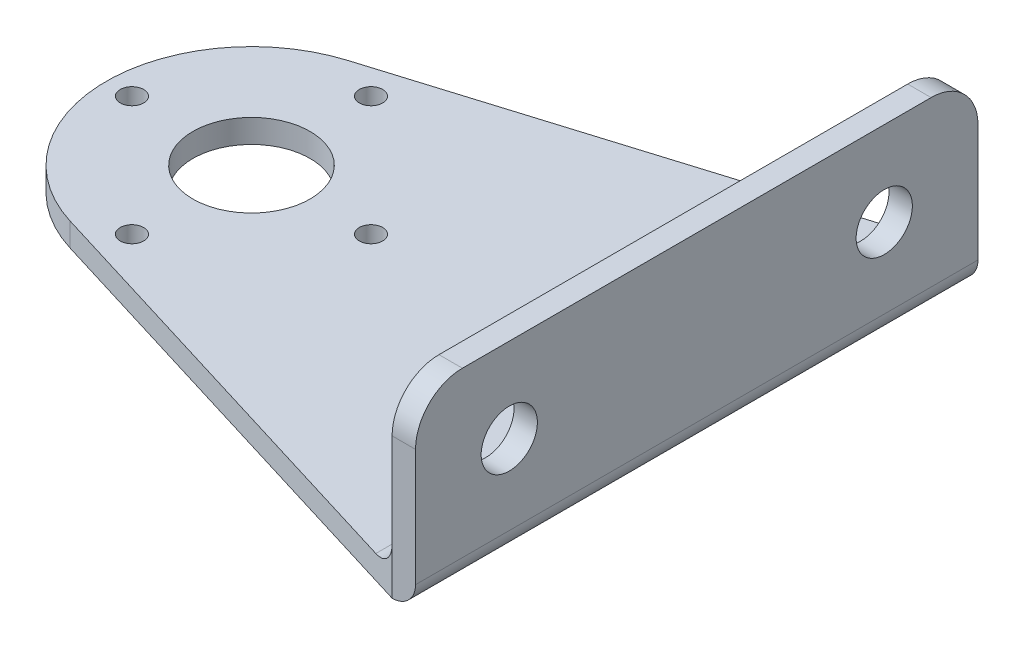
SolidWorks part; units mm, degrees
material "PBT General Purpose"
ref_plane "Front Plane" through (0, 0, 0) normal (0, 0, 1) x (1, 0, 0)
ref_plane "Top Plane" through (0, 0, 0) normal (0, 1, 0) x (1, 0, 0)
ref_plane "Right Plane" through (0, 0, 0) normal (1, 0, 0) x (0, 0, -1)
sketch "Sketch1" plane through (0, 0, 0) normal (0, 1, 0) x (1, 0, 0)
  line L0 (0, 0) -> (90, 0) construction
  line L1 (90, 60) -> (90, -60)
  line L2 (90, 60) -> (-9.0821, 29.6398)
  line L3 (90, -60) -> (-9.0821, -29.6398)
  arc A0 (-9.0821, 29.6398) -> (-9.0821, -29.6398) centre (0, 0) ccw
  circle A1 centre (0, 0) radius 25.5 construction
  circle A2 centre (0, 25.5) radius 2.5
  circle A3 centre (-25.5, 0) radius 2.5
  circle A4 centre (25.5, 0) radius 2.5
  circle A5 centre (0, -25.5) radius 2.5
  circle A6 centre (0, 0) radius 12.5
  point P7 (90, 0)
  dimension "D1" = 62
  dimension "D4" = 51
  dimension "D5" = 5
  dimension "D6" = 25
  dimension "D2" = 90
  dimension "D3" = 120
extrude "Boss-Extrude1" add sketch "Sketch1" along normal blind 5
sketch "Sketch2" plane through (90, 0, 0) normal (1, 0, 0) x (0, 0, -1)
  line L0 (60, 5) -> (60, 0) construction
  line L1 (-60, 0) -> (60, 0)
  line L2 (-60, 0) -> (-60, 30)
  line L3 (-50, 40) -> (50, 40)
  line L4 (60, 0) -> (60, 30)
  arc A0 (50, 40) -> (60, 30) centre (50, 30) cw
  arc A1 (-60, 30) -> (-50, 40) centre (-50, 30) cw
  point P9 (60, 40)
  dimension "D2" = 10
  dimension "D1" = 40
extrude "Boss-Extrude2" add sketch "Sketch2" along normal blind 5
fillet "Fillet1" radius 5 2 edges at (95, 0, 0) (90, 5, 0)
sketch "Sketch3" plane through (95, 0, 0) normal (1, 0, 0) x (0, 0, -1)
  line L0 (-40, 22) -> (40, 22) construction
  line L1 (50, 40) -> (-50, 40) construction
  circle A0 centre (-40, 22) radius 6
  circle A1 centre (40, 22) radius 6
  point P4 (0, 22)
  point P7 (0, 40)
  dimension "D3" = 12
  dimension "D4" = 12
  dimension "D1" = 80
  dimension "D2" = 18
extrude "Cut-Extrude1" cut sketch "Sketch3" against normal blind 10
